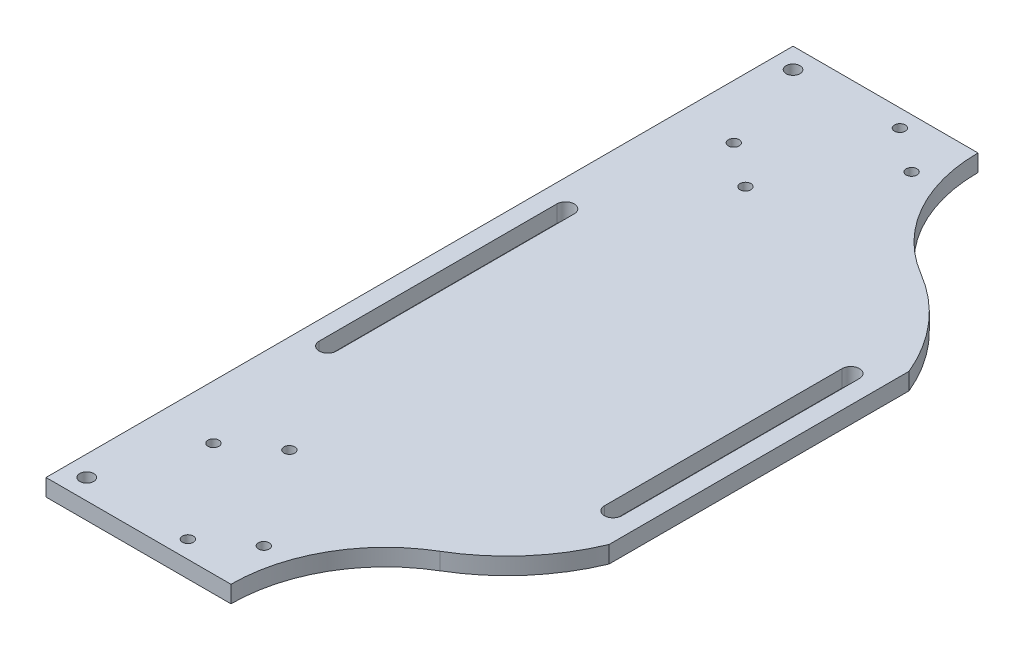
SolidWorks part; units mm, degrees
ref_plane "Front Plane" through (0, 0, 0) normal (0, 0, 1) x (1, 0, 0)
ref_plane "Top Plane" through (0, 0, 0) normal (0, 1, 0) x (1, 0, 0)
ref_plane "Right Plane" through (0, 0, 0) normal (1, 0, 0) x (0, 0, -1)
sketch "Sketch1" plane through (0, 0, 0) normal (0, 1, 0) x (1, 0, 0)
  line L0 (42, -35) -> (42, 35) construction
  line L1 (50, -110) -> (-50, -110)
  line L2 (50, -110) -> (50, 110)
  line L3 (50, 110) -> (-50, 110)
  line L4 (-50, -110) -> (-50, 110)
  line L5 (50, -110) -> (-50, 110) construction
  line L6 (50, 110) -> (-50, -110) construction
  line L7 (39.45, -35) -> (39.45, 35)
  line L8 (44.55, -35) -> (44.55, 35)
  line L9 (0, 0) -> (147.2396, 0) construction
  line L10 (-50, 110) -> (-43.1574, 104.9821) construction
  line L11 (-13.3751, 104.843) -> (-34.0728, 76.6188) construction
  line L12 (-34.0728, 76.6188) -> (-21.1704, 67.157) construction
  line L13 (-21.1704, 67.157) -> (-0.4726, 95.3812) construction
  line L14 (-0.4726, 95.3812) -> (-13.3751, 104.843) construction
  line L15 (-13.3751, 104.843) -> (-21.1704, 67.157) construction
  line L16 (-34.0728, 76.6188) -> (-0.4726, 95.3812) construction
  line L17 (0, 0) -> (0, 25) construction
  line L18 (-42, -35) -> (-42, 35) construction
  line L19 (-39.45, -35) -> (-39.45, 35)
  line L20 (-44.55, -35) -> (-44.55, 35)
  arc A0 (39.45, -35) -> (44.55, -35) centre (42, -35) ccw
  arc A1 (44.55, 35) -> (39.45, 35) centre (42, 35) ccw
  circle A2 centre (-44, 104) radius 2.05
  circle A3 centre (-34.0728, 76.6188) radius 1.6
  circle A4 centre (-0.4726, 95.3812) radius 1.6
  circle A6 centre (-21.1704, 67.157) radius 1.6
  circle A7 centre (-13.3751, 104.843) radius 1.6
  circle A8 centre (-0.4726, -95.3812) radius 1.6
  circle A9 centre (-21.1704, -67.157) radius 1.6
  circle A10 centre (-34.0728, -76.6188) radius 1.6
  circle A11 centre (-44, -104) radius 2.05
  circle A12 centre (-13.3751, -104.843) radius 1.6
  arc A13 (-39.45, -35) -> (-44.55, -35) centre (-42, -35) cw
  arc A14 (-44.55, 35) -> (-39.45, 35) centre (-42, 35) cw
  point P0 (0, 0)
  point P8 (42, 0)
  point P21 (-17.2727, 86)
  point P24 (-17.2727, 86)
  point P43 (-42, 0)
  point P48 (100, 0)
  point P49 (0, 0)
  point P50 (-23.1037, 90.2761)
  point P51 (-17.5446, 86.1993)
  dimension "D3" = 2.55
  dimension "D6" = 4.1
  dimension "D12" = 3.2
  dimension "D1" = 100
  dimension "D2" = 220
  dimension "D4" = 8
  dimension "D5" = 70
  dimension "D7" = 6
  dimension "D8" = 6
  dimension "D9" = 35
  dimension "D10" = 16
  dimension "D11" = 24
  dimension "D13" = 150
extrude "Boss-Extrude1" add sketch "Sketch1" along normal blind 5
sketch "Sketch2" plane through (0, 5, 0) normal (0, 1, 0) x (1, 0, 0)
  line L0 (50, 110) -> (-50, 110) construction
  line L1 (50, -110) -> (50, 110) construction
  line L2 (0, 0) -> (74.7594, 0) construction
  line L3 (4.4662, 110) -> (50, 110)
  line L4 (50, 110) -> (50, 44.1755)
  line L5 (50, -44.1755) -> (50, -110)
  line L6 (50, -110) -> (4.4662, -110)
  arc A0 (4.4662, 110) -> (26.8389, 70.7968) centre (50, 110) ccw
  arc A1 (26.8389, 70.7968) -> (50, 44.1755) centre (-1.5904, 22.6767) cw
  arc A2 (26.8389, -70.7968) -> (50, -44.1755) centre (-1.5904, -22.6767) ccw
  arc A3 (4.4662, -110) -> (26.8389, -70.7968) centre (50, -110) cw
extrude "Cut-Extrude1" cut sketch "Sketch2" against normal blind 10
